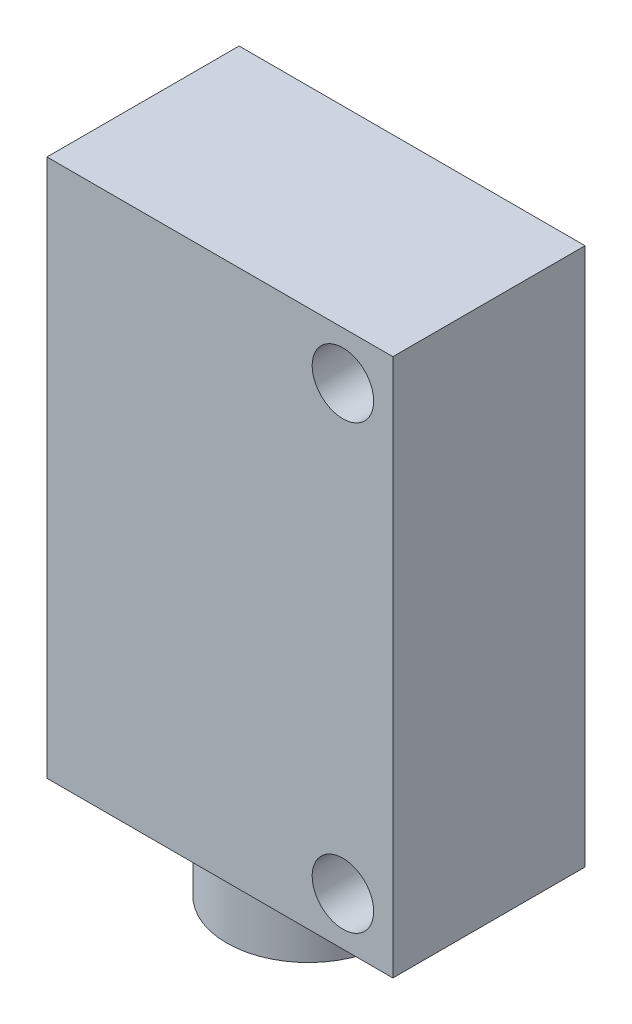
SolidWorks part; units mm, degrees
ref_plane "Plan de face" through (0, 0, 0) normal (0, 0, 1) x (1, 0, 0)
ref_plane "Plan de dessus" through (0, 0, 0) normal (0, 1, 0) x (1, 0, 0)
ref_plane "Plan de droite" through (0, 0, 0) normal (1, 0, 0) x (0, 0, -1)
sketch "Esquisse1" plane through (0, 0, 0) normal (0, 0, 1) x (1, 0, 0)
  line L1 (0, 0) -> (18, 0)
  line L2 (0, 0) -> (0, 28)
  line L3 (0, 28) -> (18, 28)
  line L4 (18, 0) -> (18, 28)
extrude "Boss.-Extru.1" add sketch "Esquisse1" along normal blind 10
sketch "Esquisse3" plane through (0, 0, 0) normal (0, -1, 0) x (1, 0, 0)
  circle A0 centre (8.6, 5) radius 4.25
extrude "Boss.-Extru.2" add sketch "Esquisse3" along normal blind 3.5 contours A0
sketch "Esquisse4" plane through (0, 0, 0) normal (0, 0, -1) x (-1, 0, 0)
  line L0 (-18, 28) -> (0, 28) construction
  line L1 (-18, 0) -> (-18, 28) construction
  line L3 (0, 28) -> (0, 0) construction
  circle A0 centre (-15.4, 25.5) radius 1.6
  dimension "D1" = 2.5
  dimension "D2" = 2.6
  dimension "D3" = 15.4
extrude "Enlèv. mat.-Extru.1" cut sketch "Esquisse4" against normal blind 10.2
sketch "Esquisse5" plane through (0, 0, 0) normal (0, 0, -1) x (-1, 0, 0)
  circle A0 centre (-15.4, 2.5) radius 1.6
extrude "Enlèv. mat.-Extru.2" cut sketch "Esquisse5" against normal blind 10.2
sketch "Esquisse6" plane through (0, 0, 0) normal (-1, 0, 0) x (0, 0, 1)
  line L1 (1.7369, 25.6158) -> (8.6193, 25.6158)
  line L2 (1.7369, 25.6158) -> (1.7369, 2.1259)
  line L3 (1.7369, 2.1259) -> (8.6193, 2.1259)
  line L4 (8.6193, 25.6158) -> (8.6193, 2.1259)
extrude "Boss.-Extru.3" add sketch "Esquisse6" along normal blind 1
